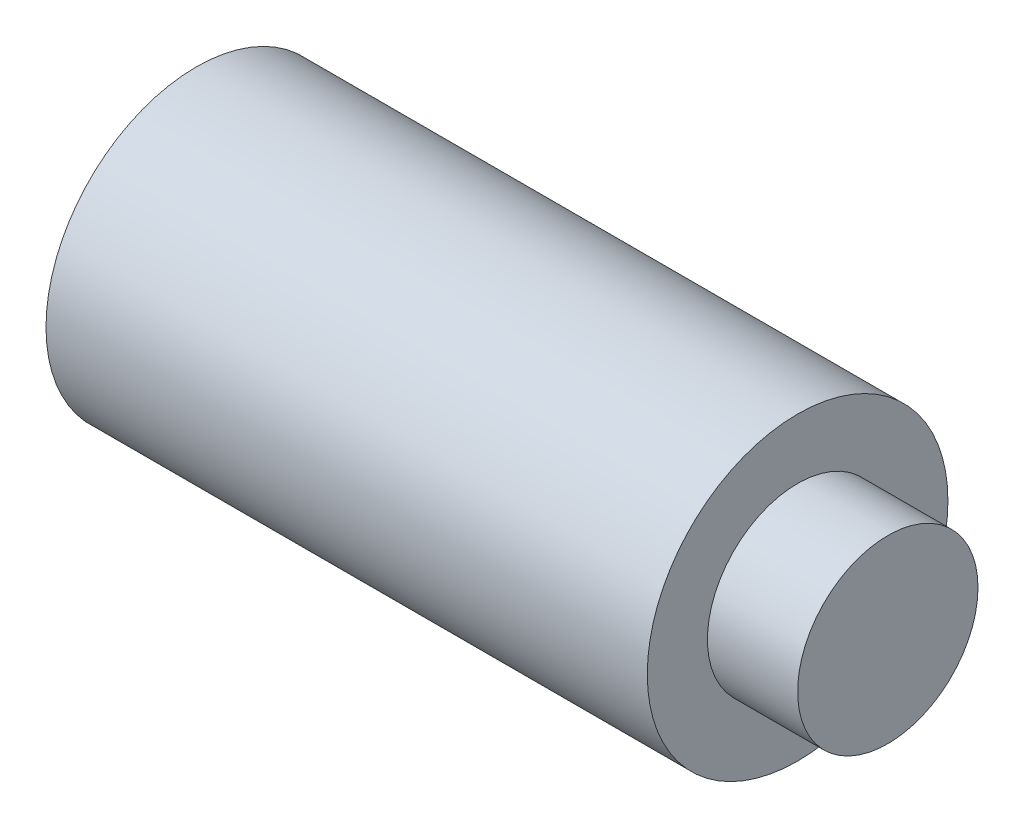
SolidWorks part; units mm, degrees
ref_plane "前视基准面" through (0, 0, 0) normal (0, 0, 1) x (1, 0, 0)
ref_plane "上视基准面" through (0, 0, 0) normal (0, 1, 0) x (1, 0, 0)
ref_plane "右视基准面" through (0, 0, 0) normal (1, 0, 0) x (0, 0, -1)
other "Configuration Table"
sketch "草图1" plane through (0, 0, 0) normal (1, 0, 0) x (0, 0, -1)
  circle A0 centre (0, 0) radius 2.5
  dimension "D1" = 5
extrude "凸台-拉伸1" add sketch "草图1" along normal mid plane 10
sketch "草图2" plane through (0, 0, 0) normal (1, 0, 0) x (0, 0, -1)
  circle A0 centre (0, 0) radius 1.5
  dimension "D1" = 3
extrude "切除-拉伸1" cut sketch "草图2" against normal blind 15
sketch "草图3" plane through (5, 0, 0) normal (1, 0, 0) x (0, 0, -1)
  circle A0 centre (0, 0) radius 1.5
  dimension "D1" = 3
extrude "凸台-拉伸4" add sketch "草图3" along normal mid plane 3
